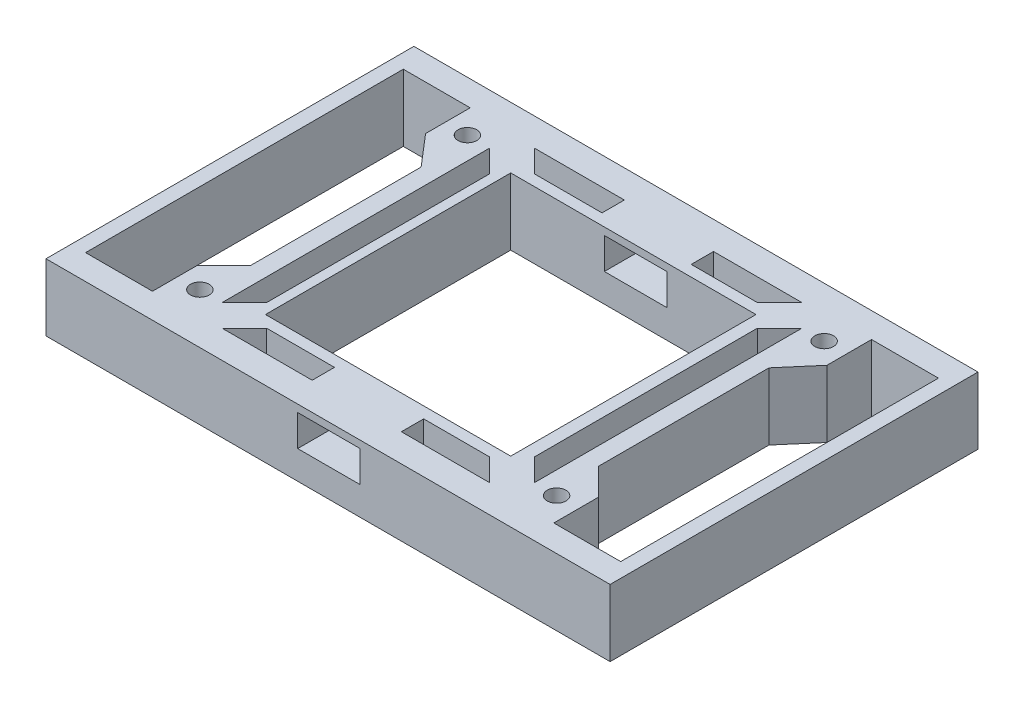
SolidWorks part; units mm, degrees
ref_plane "Спереди" through (0, 0, 0) normal (0, 0, 1) x (1, 0, 0)
ref_plane "Сверху" through (0, 0, 0) normal (0, 1, 0) x (1, 0, 0)
ref_plane "Справа" through (0, 0, 0) normal (1, 0, 0) x (0, 0, -1)
ref_plane "Плоскость4" through (0, 45.646, 0) normal (0, -1, 0) x (-1, 0, 0)
sketch "Эскиз1" plane through (0, 45.646, 0) normal (0, -1, 0) x (-1, 0, 0)
  line L2 (-1.559, -130.7731) -> (-128.059, -130.7731) construction
  line L3 (-29.809, -130.7731) -> (-99.809, -130.7731)
  line L7 (-128.059, -48.2731) -> (-96.309, -48.2731) construction
  line L8 (-99.809, -48.2731) -> (-29.809, -48.2731)
  line L9 (-93.309, -48.2731) -> (-1.559, -48.2731) construction
  line L11 (-19.809, -48.2731) -> (-19.809, -53.8981)
  line L12 (-19.809, -48.2731) -> (-29.809, -48.2731)
  line L13 (-19.809, -125.1481) -> (-19.809, -53.8981)
  line L14 (-19.809, -130.7731) -> (-19.809, -125.1481)
  line L15 (-29.809, -130.7731) -> (-19.809, -130.7731)
  line L16 (-19.809, -130.7731) -> (-1.559, -130.7731)
  line L17 (-1.559, -130.7731) -> (-1.559, -48.2731)
  line L18 (-1.559, -48.2731) -> (-19.809, -48.2731)
  line L21 (-109.809, -130.7731) -> (-99.809, -130.7731)
  line L22 (-109.809, -130.7731) -> (-128.059, -130.7731)
  line L23 (-128.059, -130.7731) -> (-128.059, -48.2731) construction
  line L24 (-128.059, -130.7731) -> (-128.059, -48.2731)
  line L25 (-128.059, -48.2731) -> (-109.809, -48.2731)
  line L27 (-99.809, -48.2731) -> (-110.4127, -48.2731)
  line L28 (-92, -62) -> (-37, -62)
  line L29 (-64.809, -54.5231) -> (-29.809, -54.5231)
  line L30 (-92, -62) -> (-92, -117)
  line L31 (-92, -117) -> (-37, -117)
  line L32 (-37, -117) -> (-37, -62)
  line L33 (-64.809, -54.5231) -> (-99.809, -54.5231)
  line L34 (-64.809, -124.5231) -> (-29.809, -124.5231)
  line L35 (-64.809, -124.5231) -> (-99.809, -124.5231)
  line L36 (-19.809, -53.8981) -> (-4.809, -53.8981)
  line L37 (-19.809, -125.1481) -> (-4.809, -125.1481)
  line L38 (-4.809, -125.1481) -> (-4.809, -53.8981)
  line L39 (-109.809, -53.8981) -> (-124.809, -53.8981)
  line L40 (-109.809, -125.1481) -> (-124.809, -125.1481)
  line L41 (-124.809, -125.1481) -> (-124.809, -53.8981)
  line L42 (-29.809, -48.2731) -> (-29.809, -54.5231)
  line L43 (-29.809, -124.5231) -> (-29.809, -54.5231)
  line L44 (-29.809, -130.7731) -> (-29.809, -124.5231)
  line L45 (-109.809, -48.2731) -> (-109.809, -53.8981)
  line L46 (-109.809, -125.1481) -> (-109.809, -53.8981)
  line L47 (-109.809, -130.7731) -> (-109.809, -125.1481)
  line L48 (-99.809, -130.7731) -> (-99.809, -124.5231)
  line L49 (-99.809, -54.5231) -> (-99.809, -124.5231)
  line L50 (-99.809, -54.5231) -> (-99.809, -48.2731)
  line L51 (-34.809, -59.5231) -> (-94.809, -59.5231)
  line L52 (-94.809, -59.5231) -> (-94.809, -119.5231)
  line L53 (-34.809, -59.5231) -> (-34.809, -119.5231)
  line L54 (-34.809, -119.5231) -> (-94.809, -119.5231)
  line L55 (-64.809, -54.5231) -> (-55, -54.5231)
  line L56 (-55, -54.5231) -> (-55, -59.5231)
  line L57 (-75, -124.5231) -> (-75, -119.5231)
  line L58 (-55, -119.5231) -> (-55, -124.5231)
  line L59 (-55, -124.5231) -> (-75, -124.5231)
  line L60 (-55, -59.5231) -> (-75, -59.5231)
  line L61 (-75, -59.5231) -> (-75, -54.5231)
  line L62 (-99.809, -95.5231) -> (-94.809, -95.5231)
  line L63 (-94.809, -89.5231) -> (-94.809, -83.5231)
  line L64 (-94.809, -83.5231) -> (-99.809, -83.5231)
  line L65 (-99.809, -83.5231) -> (-99.809, -95.5231)
  line L66 (-29.809, -95.5231) -> (-34.809, -95.5231)
  line L67 (-29.809, -95.5231) -> (-29.809, -83.5231)
  line L68 (-29.809, -83.5231) -> (-34.809, -83.5231)
  line L69 (-94.809, -59.5231) -> (-94.809, -64.5231)
  line L70 (-94.809, -59.5231) -> (-89.809, -59.5231)
  line L71 (-99.809, -54.5231) -> (-94.809, -54.5231)
  line L72 (-99.809, -54.5231) -> (-99.809, -59.5231)
  line L73 (-99.809, -59.5231) -> (-94.809, -64.5231)
  line L74 (-94.809, -54.5231) -> (-89.809, -59.5231)
  line L75 (-34.809, -59.5231) -> (-34.809, -64.5231)
  line L76 (-29.809, -54.5231) -> (-29.809, -59.5231)
  line L77 (-29.809, -54.5231) -> (-34.809, -54.5231)
  line L78 (-34.809, -59.5231) -> (-39.809, -59.5231)
  line L79 (-39.809, -59.5231) -> (-34.809, -54.5231)
  line L80 (-34.809, -64.5231) -> (-29.809, -59.5231)
  line L81 (-34.809, -119.5231) -> (-34.809, -114.5231)
  line L82 (-29.809, -124.5231) -> (-29.809, -119.5231)
  line L83 (-34.809, -119.5231) -> (-39.809, -119.5231)
  line L84 (-29.809, -124.5231) -> (-34.809, -124.5231)
  line L85 (-34.809, -124.5231) -> (-39.809, -119.5231)
  line L86 (-34.809, -114.5231) -> (-29.809, -119.5231)
  line L87 (-94.809, -119.5231) -> (-89.809, -119.5231)
  line L88 (-94.809, -119.5231) -> (-94.809, -114.5231)
  line L89 (-99.809, -124.5231) -> (-99.809, -119.5231)
  line L90 (-99.809, -124.5231) -> (-94.809, -124.5231)
  line L91 (-94.809, -124.5231) -> (-89.809, -119.5231)
  line L92 (-99.809, -119.5231) -> (-94.809, -114.5231)
  circle A0 centre (-104.809, -59.5231) radius 2.1
  circle A2 centre (-24.809, -59.5231) radius 2.1
  circle A4 centre (-24.809, -119.5231) radius 2.1
  circle A6 centre (-104.809, -119.5231) radius 2.1
extrude "Бобышка-Вытянуть1" add sketch "Эскиз1" along normal blind 15 contours L22 L47 L40 L41 L39 L45 L25 L24 | L49 L50 L27 L45 L46 L47 L21 L48 A6 A0 | L54 L53 L51 L52 L32 L31 L30 L28 | L58 L54 L57 L35 L34 | L48 L3 L44 L34 L35 | L50 L33 L29 L42 L8 | L44 L15 L14 L13 L11 L12 L42 L43 A4 A2 | L38 L37 L14 L16 L17 L18 L11 L36 | L92 L49 L35 L91 L54 L52 | L86 L53 L54 L85 L34 L43 | L53 L80 L43 L29 L79 L51 | L74 L33 L49 L73 L52 L51 | L61 L51 L56 L29 L33
ref_plane "Плоскость5" through (0, 0, 130.7731) normal (0, 0, 1) x (1, 0, 0)
sketch "Эскиз2" plane through (0, 0, 130.7731) normal (0, 0, 1) x (1, 0, 0)
  line L1 (64.809, 44) -> (72, 44)
  line L2 (72, 44) -> (72, 37)
  line L3 (72, 37) -> (58, 37)
  line L4 (58, 37) -> (58, 44)
  line L5 (58, 44) -> (64.809, 44)
extrude "Вырез-Вытянуть1" cut sketch "Эскиз2" against normal through all both and the other way through all
ref_plane "Плоскость6" through (0, 45.646, 0) normal (0, 1, 0) x (1, 0, 0)
sketch "Эскиз3" plane through (0, 45.646, 0) normal (0, 1, 0) x (1, 0, 0)
  line L1 (19.809, -125.1481) -> (19.809, -53.8981) construction
  line L6 (103.809, -70.8981) -> (103.809, -109.1481)
  line L7 (25.809, -70.8981) -> (25.809, -109.1481)
  line L8 (25.809, -109.1481) -> (19.809, -115.1481)
  line L9 (19.809, -63.8981) -> (25.809, -70.8981)
  line L10 (19.809, -63.8981) -> (19.809, -115.1481)
  line L12 (109.809, -53.8981) -> (109.809, -125.1481) construction
  line L14 (109.809, -115.1481) -> (103.809, -109.1481)
  line L15 (103.809, -70.8981) -> (109.809, -63.8981)
  line L16 (109.809, -63.8981) -> (109.809, -115.1481)
extrude "Вырез-Вытянуть2" cut sketch "Эскиз3" against normal through all both and the other way through all
